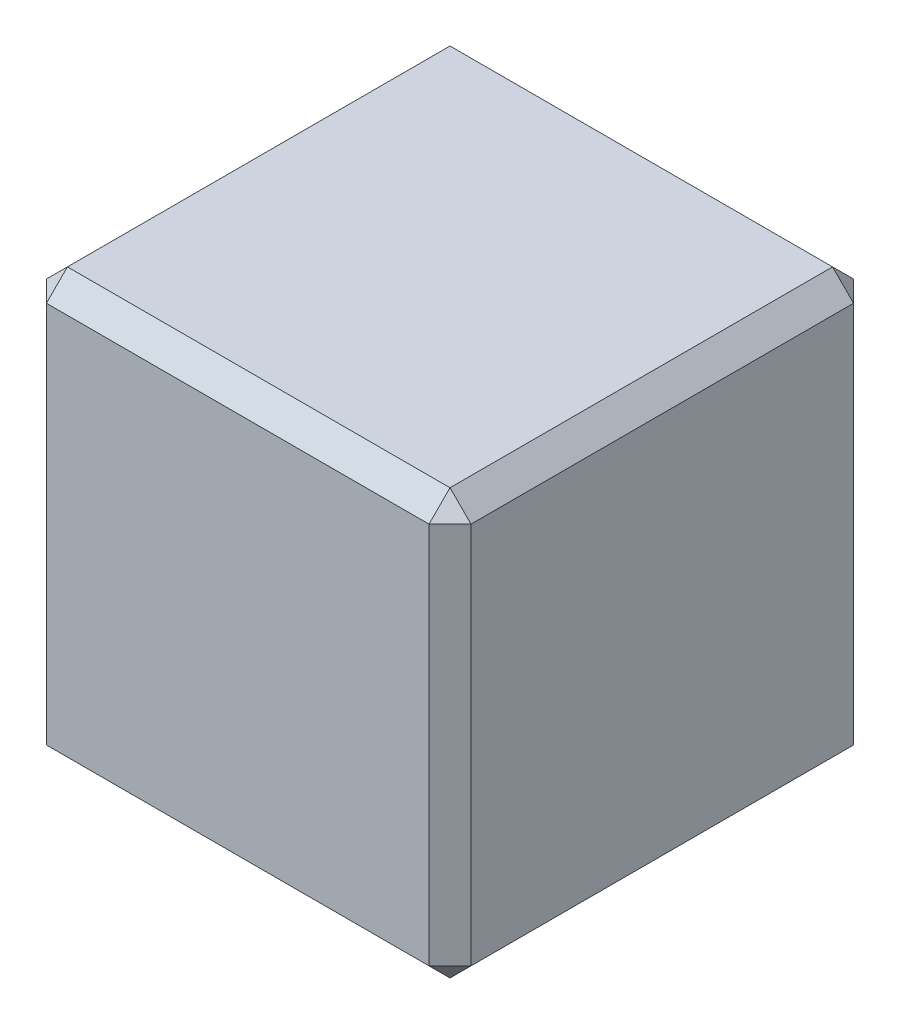
SolidWorks part; units mm, degrees
ref_plane "前视基准面" through (0, 0, 0) normal (0, 0, 1) x (1, 0, 0)
ref_plane "上视基准面" through (0, 0, 0) normal (0, 1, 0) x (1, 0, 0)
ref_plane "右视基准面" through (0, 0, 0) normal (1, 0, 0) x (0, 0, -1)
sketch "草图1" plane through (0, 0, 0) normal (0, 1, 0) x (1, 0, 0)
  line L1 (-50.54, 50.54) -> (50.54, 50.54)
  line L2 (-50.54, 50.54) -> (-50.54, -50.54)
  line L3 (-50.54, -50.54) -> (50.54, -50.54)
  line L4 (50.54, 50.54) -> (50.54, -50.54)
  line L5 (0, -50.54) -> (0, 50.54) construction
  line L6 (-50.54, 0) -> (50.54, 0) construction
  point P0 (0, 0)
  dimension "D1" = 101.08
extrude "凸台-拉伸1" add sketch "草图1" along normal blind 101.08
chamfer "倒角1" distance 5 angle 45 12 edges at (0, 0, -50.54) (50.54, 50.54, -50.54) (50.54, 0, 0) (50.54, 50.54, 50.54) (0, 0, 50.54) (-50.54, 50.54, -50.54) (-50.54, 0, 0) (-50.54, 50.54, 50.54) (0, 101.08, 50.54) (-50.54, 101.08, 0) (0, 101.08, -50.54) (50.54, 101.08, 0)
